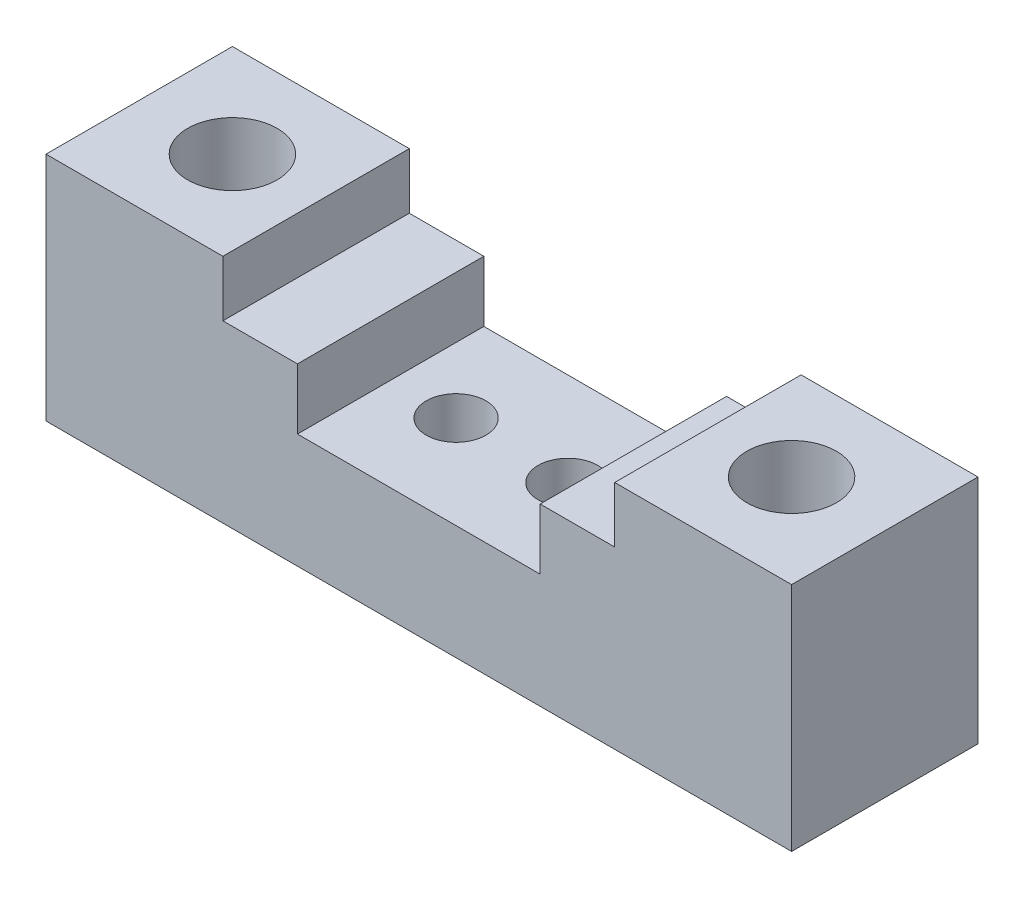
SolidWorks part; units mm, degrees
ref_plane "Front Plane" through (0, 0, 0) normal (0, 0, 1) x (1, 0, 0)
ref_plane "Top Plane" through (0, 0, 0) normal (0, 1, 0) x (1, 0, 0)
ref_plane "Right Plane" through (0, 0, 0) normal (1, 0, 0) x (0, 0, -1)
sketch "Sketch1" plane through (0, 0, 0) normal (0, 1, 0) x (1, 0, 0)
  line L1 (-10, -2.5) -> (10, -2.5)
  line L2 (-10, -2.5) -> (-10, 2.5)
  line L3 (-10, 2.5) -> (10, 2.5)
  line L4 (10, -2.5) -> (10, 2.5)
  line L5 (-10, -2.5) -> (10, 2.5) construction
  line L6 (-10, 2.5) -> (10, -2.5) construction
  point P0 (0, 0)
  dimension "D1" = 20
  dimension "D2" = 5
extrude "Extrude1" add sketch "Sketch1" along normal blind 6.2
sketch "Sketch2" plane through (0, 6.2, 0) normal (0, 1, 0) x (1, 0, 0)
  line L0 (10, 2.5) -> (-10, 2.5) construction
  line L1 (-5.255, -2.5) -> (5.255, -2.5)
  line L2 (-5.255, -2.5) -> (-5.255, 2.5)
  line L3 (-5.255, 2.5) -> (5.255, 2.5)
  line L4 (5.255, -2.5) -> (5.255, 2.5)
  line L5 (-5.255, -2.5) -> (5.255, 2.5) construction
  line L6 (-5.255, 2.5) -> (5.255, -2.5) construction
  point P0 (0, 0)
  dimension "D1" = 10.51
extrude "Extrude3" cut sketch "Sketch2" against normal blind 1.5
sketch "Sketch3" plane through (0, 4.7, 0) normal (0, 1, 0) x (1, 0, 0)
  line L0 (5.255, 2.5) -> (-5.255, 2.5) construction
  line L1 (-3.255, -2.5) -> (3.255, -2.5)
  line L2 (-3.255, -2.5) -> (-3.255, 2.5)
  line L3 (-3.255, 2.5) -> (3.255, 2.5)
  line L4 (3.255, -2.5) -> (3.255, 2.5)
  line L5 (-3.255, -2.5) -> (3.255, 2.5) construction
  line L6 (-3.255, 2.5) -> (3.255, -2.5) construction
  point P0 (0, 0)
  dimension "D1" = 6.51
extrude "Extrude4" cut sketch "Sketch3" against normal blind 1.63
sketch "Sketch7" plane through (0, 0, 0) normal (0, -1, 0) x (1, 0, 0)
  line L0 (-11.8618, 0) -> (13.4266, 0) construction
  line L1 (0, 5.1538) -> (0, -5.1425) construction
hole_wizard "CBORE for M2 SHCS1" positions "3DSketch1" profile "Sketch4" counterbore size "M2" standard "Ansi Metric" end condition through all
sketch3d "3DSketch1"
  line L1 (-11.8618, 0, 0) -> (13.4266, 0, 0) construction
  line L2 (0, 0, 5.1538) -> (0, 0, -5.1425) construction
  point P8 (-7.5, 0, 0)
  dimension "D1" = 7.5
sketch "Sketch4" plane through (-7.5, 0, 0) normal (1, 0, 0) x (0, 0, -1)
  line L0 (0, 0) -> (0, 6.2)
  line L1 (0, 6.2) -> (1.2, 6.2)
  line L3 (1.2, 6.2) -> (1.2, 2)
  line L4 (1.2, 2) -> (2.2, 2)
  line L5 (2.2, 2) -> (2.2, 0)
  line L7 (2.2, 0) -> (0, 0)
  line L11 (0, -6.35) -> (0, 107.95) construction
  dimension "Thru Hole Dia." = 2.4
  dimension "Thru Hole Depth" = 6.2
  dimension "C'Bore Dia." = 4.4
  dimension "C'Bore Depth" = 2
sketch "Sketch5" plane through (0, 0, 0) normal (0, -1, 0) x (1, 0, 0)
  line L0 (-11.6367, 0) -> (12.8569, 0) construction
  line L1 (0, 4.5269) -> (0, -3.9986) construction
pattern_linear "LPattern1" count 2 spacing 15 along (1, 0, 0) of "CBORE for M2 SHCS1"
hole_wizard "M2x0.4 Tapped Hole1" positions "3DSketch2" profile "Sketch6" tap size "M2x0.4" standard "Ansi Metric" end condition through all
sketch3d "3DSketch2"
  line L0 (-11.6367, 0, 0) -> (12.8569, 0, 0) construction
  line L1 (0, 0, 4.5269) -> (0, 0, -3.9986) construction
  point P0 (-1.5, 0, 0)
  dimension "D1" = 1.5
sketch "Sketch6" plane through (-1.5, 0, 0) normal (1, 0, 0) x (0, 0, -1)
  line L0 (0, 0) -> (0, 6.2)
  line L1 (0, 6.2) -> (0.8, 6.2)
  line L2 (0.8, 6.2) -> (0.8, 0)
  line L5 (0.8, 0) -> (0, 0)
  line L11 (0, -6.35) -> (0, 107.95) construction
  dimension "Thread Major Dia." = 1.6
  dimension "Thru Tap Drill Depth" = 6.2
pattern_linear "LPattern3" count 2 spacing 3 along (1, 0, 0) of "M2x0.4 Tapped Hole1"
